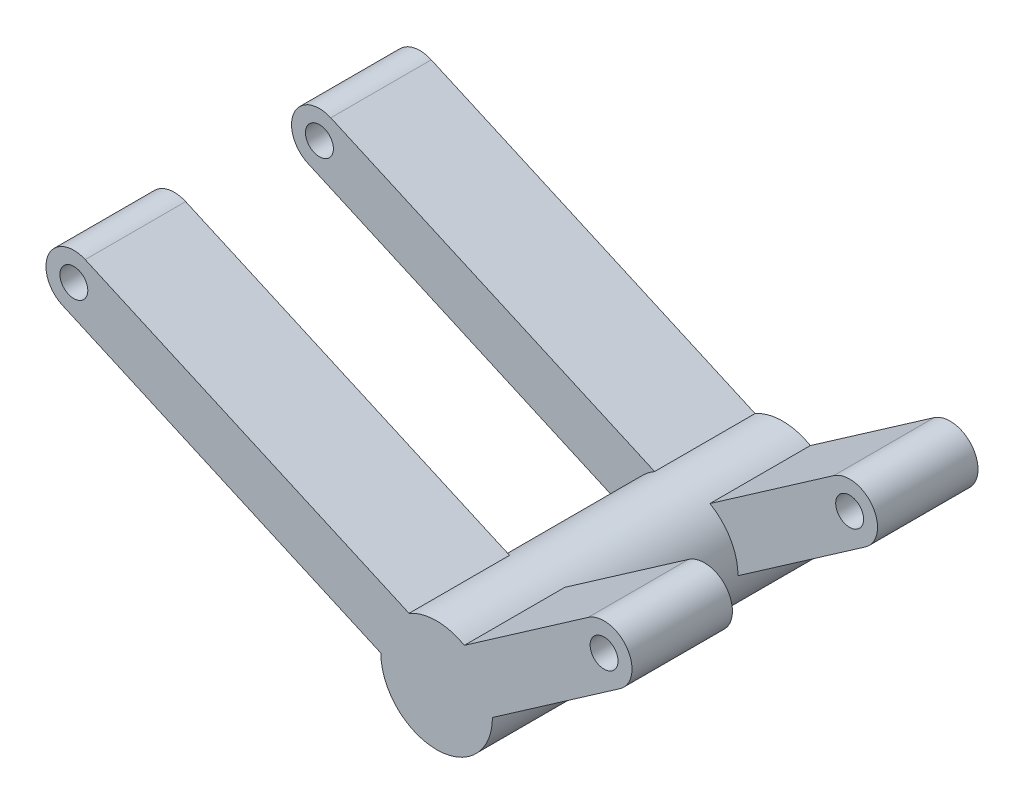
SolidWorks part; units mm, degrees
ref_plane "Front Plane" through (0, 0, 0) normal (0, 0, 1) x (1, 0, 0)
ref_plane "Top Plane" through (0, 0, 0) normal (0, 1, 0) x (1, 0, 0)
ref_plane "Right Plane" through (0, 0, 0) normal (1, 0, 0) x (0, 0, -1)
sketch "Sketch1" plane through (0, 0, 0) normal (0, 0, 1) x (1, 0, 0)
  circle A2 centre (0, 0) radius 5
  dimension "D1" = 10
extrude "Boss-Extrude3" add sketch "Sketch1" along normal mid plane 13 contours A2
sketch "Sketch3" plane through (0, 0, 6.5) normal (0, 0, 1) x (1, 0, 0)
  line L0 (5, 0) -> (16.4274, 7.9476)
  line L1 (13.5726, 12.0524) -> (2.4831, 4.3399)
  line L2 (-5, 0) -> (-33.5182, 12.7167)
  line L3 (-31.4818, 17.2833) -> (-2.4709, 4.3468)
  line L4 (-17.0529, 0) -> (-7.667, 0) construction
  circle A0 centre (0, 0) radius 5 construction
  arc A1 (16.4274, 7.9476) -> (13.5726, 12.0524) centre (15, 10) ccw
  arc A2 (-33.5182, 12.7167) -> (-31.4818, 17.2833) centre (-32.5, 15) cw
  arc A3 (-2.4709, 4.3468) -> (2.4831, 4.3399) centre (0, 0) cw
  arc A4 (-5, 0) -> (5, 0) centre (0, 0) ccw
  arc A5 (5, 0) -> (-5, 0) centre (0, 0) cw
  circle A6 centre (-32.5, 15) radius 1.25
  circle A7 centre (15, 10) radius 1.25
  point P6 (0, 0)
  point P19 (0, 0)
  point P20 (0, 0)
  point P21 (-2.4632, 4.3512)
  point P22 (0, 0)
  dimension "D2" = 2.5
  dimension "D3" = 10
  dimension "D7" = 2.5
  dimension "D4" = 15
  dimension "D5" = 32.5
  dimension "D6" = 15
  dimension "D8" = 10
extrude "Boss-Extrude4" add sketch "Sketch3" along normal blind 9
mirror "Mirror12" about plane through (0, 0, 0) normal (0, 0, 1) of "Boss-Extrude4"
